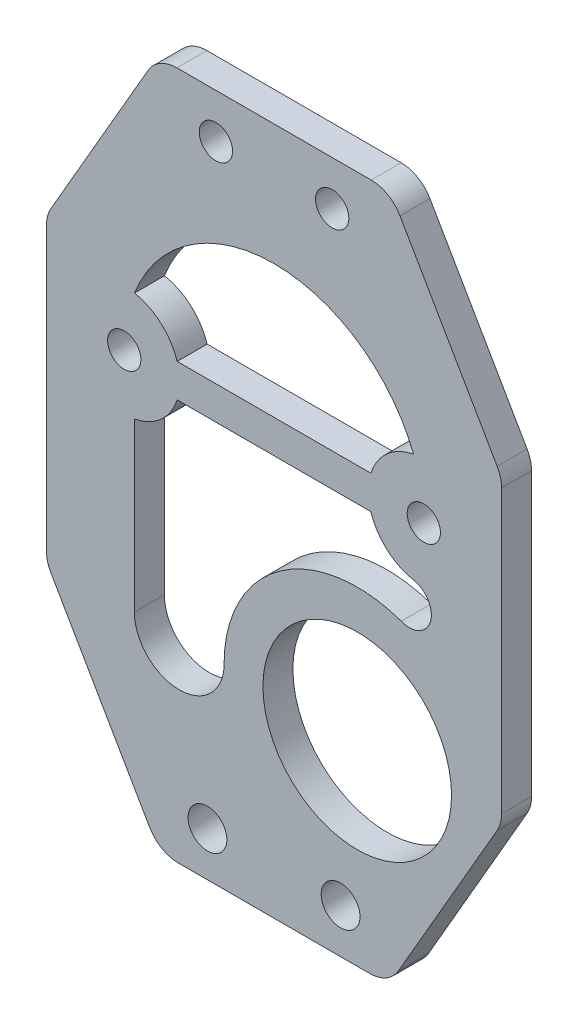
SolidWorks part; units mm, degrees
ref_plane "Front Plane" through (0, 0, 0) normal (0, 0, 1) x (1, 0, 0)
ref_plane "Top Plane" through (0, 0, 0) normal (0, 1, 0) x (1, 0, 0)
ref_plane "Right Plane" through (0, 0, 0) normal (1, 0, 0) x (0, 0, -1)
sketch "Sketch1" plane through (0, 0, 0) normal (0, 0, 1) x (1, 0, 0)
  line L0 (0, 34.1829) -> (0, -31) construction
  line L1 (-10.4877, 31) -> (10.4877, 31)
  line L2 (10.4877, 31) -> (20.1081, 14.337)
  line L3 (20.51, 12.837) -> (20.51, -12.5962)
  line L4 (20.1081, -14.0962) -> (10.3486, -31)
  line L5 (10.3486, -31) -> (-10.3486, -31)
  line L6 (-10.3486, -31) -> (-20.1081, -14.0962)
  line L7 (-20.51, -12.5962) -> (-20.51, 12.837)
  line L8 (-20.1081, 14.337) -> (-10.4877, 31)
  line L9 (-28.5813, 0) -> (26.9329, 0) construction
  line L10 (-12.58, -13.4) -> (-12.58, 1.6854)
  line L11 (-8.7303, 5.1) -> (8.7299, 5.1)
  line L12 (-8.7303, 8.1) -> (8.7299, 8.1)
  circle A0 centre (-5.24, 27) radius 1.5
  circle A1 centre (5.24, 27) radius 1.5
  circle A2 centre (-6, -27) radius 1.75
  circle A3 centre (6, -27) radius 1.75
  circle A4 centre (-13.5, 6.6) radius 1.5
  circle A5 centre (13.5, 6.6) radius 1.5
  circle A6 centre (7.5, -13.4) radius 8.5
  arc A7 (11.6226, -2.1304) -> (-4.5, -13.4) centre (7.5, -13.4) ccw
  arc A8 (11.4699, -2.0757) -> (12.5746, 1.686) centre (12.21, -0.25) ccw
  arc A9 (-12.58, -13.4) -> (-4.5, -13.4) centre (-8.54, -13.4) ccw
  arc A10 (-12.58, 1.6854) -> (-8.7303, 5.1) centre (-13.5, 6.6) ccw
  arc A11 (12.5739, 11.5139) -> (8.7299, 8.1) centre (13.5, 6.6) ccw
  arc A13 (12.5739, 11.5139) -> (-12.5741, 11.5135) centre (0, 6.6) ccw
  arc A14 (8.7299, 5.1) -> (12.5746, 1.686) centre (13.5, 6.6) ccw
  arc A15 (-8.7303, 8.1) -> (-12.5741, 11.5135) centre (-13.5, 6.6) ccw
  arc A16 (-20.1081, -14.0962) -> (-20.51, -12.5962) centre (-17.51, -12.5962) cw
  arc A17 (20.51, -12.5962) -> (20.1081, -14.0962) centre (17.51, -12.5962) cw
  arc A18 (20.1081, 14.337) -> (20.51, 12.837) centre (17.51, 12.837) cw
  arc A19 (-20.51, 12.837) -> (-20.1081, 14.337) centre (-17.51, 12.837) cw
  point P31 (0, 31)
  point P32 (-7.0503, -31)
  point P50 (20.51, -13.4)
  point P53 (20.51, 13.6408)
  point P56 (-20.51, 13.6408)
  dimension "D4" = 3
  dimension "D8" = 20.4
  dimension "D9" = 27
  dimension "D10" = 7.93
  dimension "D13" = 17
  dimension "D14" = 24
  dimension "D17" = 3.94
  dimension "D23" = 8.08
  dimension "D24" = 10
  dimension "D25" = 1.5
  dimension "D27" = 3.5
  dimension "D22" = 3
  dimension "D2" = 31
  dimension "D3" = 10.48
  dimension "D5" = 4
  dimension "D6" = 12
  dimension "D7" = 4
  dimension "D11" = 7.5
  dimension "D12" = 17.6
  dimension "D15" = 13.15
  dimension "D16" = 4.71
  dimension "D18" = 120
  dimension "D19" = 120
  dimension "D20" = 120
  dimension "D21" = 62
  dimension "D26" = 1.5
extrude "Boss-Extrude1" add sketch "Sketch1" along normal blind 2.7 contours A19 L7 A16 L6 L5 L4 A17 L3 A18 L2 L1 L8 A6 A5 A4 A3 A2 A1 A0 L11 A14 A8 A7 A9 L10 A10 L12 A15 A13 A11
fillet "Fillet1" radius 3 4 edges at (-10.3486, -31, 1.35) (10.3486, -31, 1.35) (10.4877, 31, 1.35) (-10.4877, 31, 1.35)
